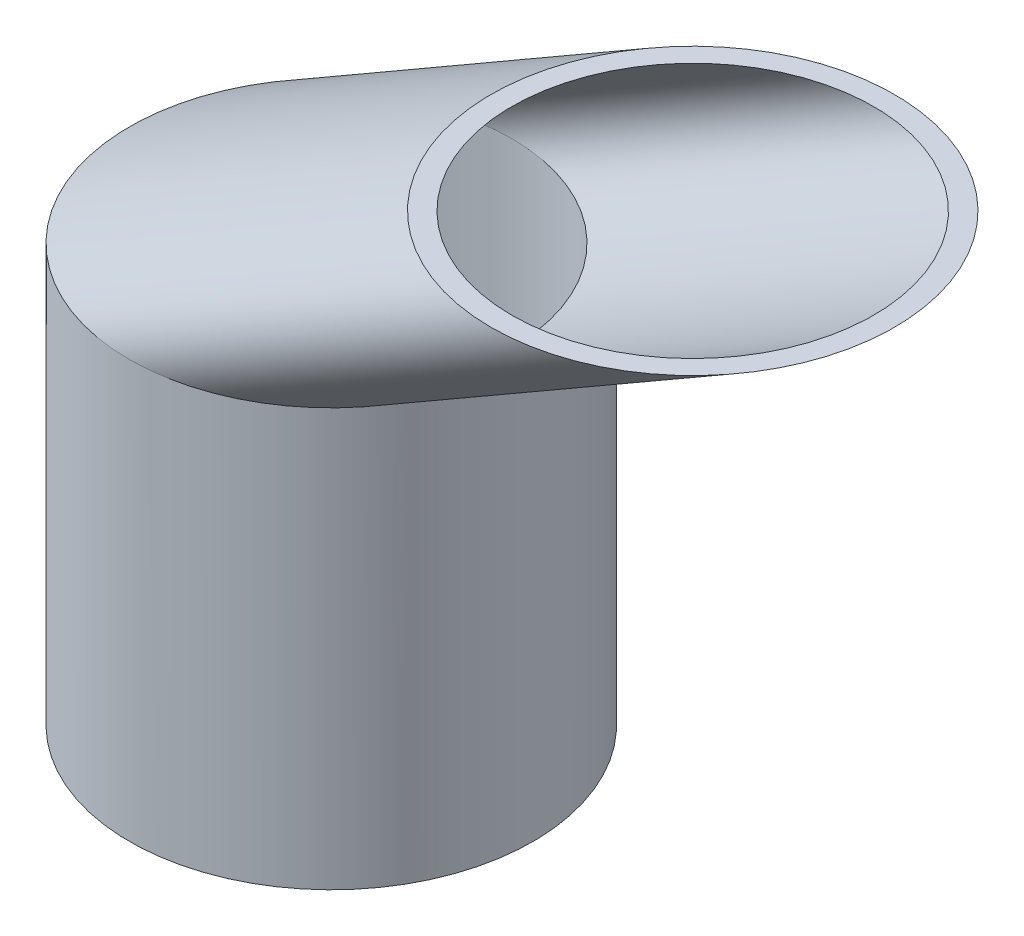
SolidWorks part; units mm, degrees
ref_plane "Front Plane" through (0, 0, 0) normal (0, 0, 1) x (1, 0, 0)
ref_plane "Top Plane" through (0, 0, 0) normal (0, 1, 0) x (1, 0, 0)
ref_plane "Right Plane" through (0, 0, 0) normal (1, 0, 0) x (0, 0, -1)
sketch "Sketch2" plane through (0, 0, 0) normal (0, 1, 0) x (1, 0, 0)
  circle A0 centre (0, 0) radius 16.51
  circle A1 centre (0, 0) radius 18.415
  dimension "D1" = 36.83
  dimension "D2" = 33.02
extrude "Boss-Extrude1" add sketch "Sketch2" along normal blind 38.1
sketch "Sketch4" plane through (0, 38.1, 0) normal (0, 1, 0) x (1, 0, 0)
  line L0 (18.415, 0) -> (18.415, 17.7789) construction
  line L1 (18.415, 17.7789) -> (18.415, -15.7736) construction
  circle A0 centre (0, 0) radius 18.415 construction
ref_plane "Plane1" through (30.309, 17.4989, 0) normal (0.866, 0.5, 0) x (0, 0, -1)
sketch "Sketch5" plane through (30.309, 17.4989, 0) normal (0.866, 0.5, 0) x (0, 0, -1)
  point P9 (0, 23.7881)
  point P14 (0, 3.1021)
sketch "Sketch7" plane through (0, 38.1, 0) normal (0, 1, 0) x (1, 0, 0)
  circle A0 centre (0, 0) radius 18.415
  circle A1 centre (0, 0) radius 16.51
extrude "Boss-Extrude5" add sketch "Sketch7" along direction (0.866, 0.5, 0) on the side of the normal blind 38.1
